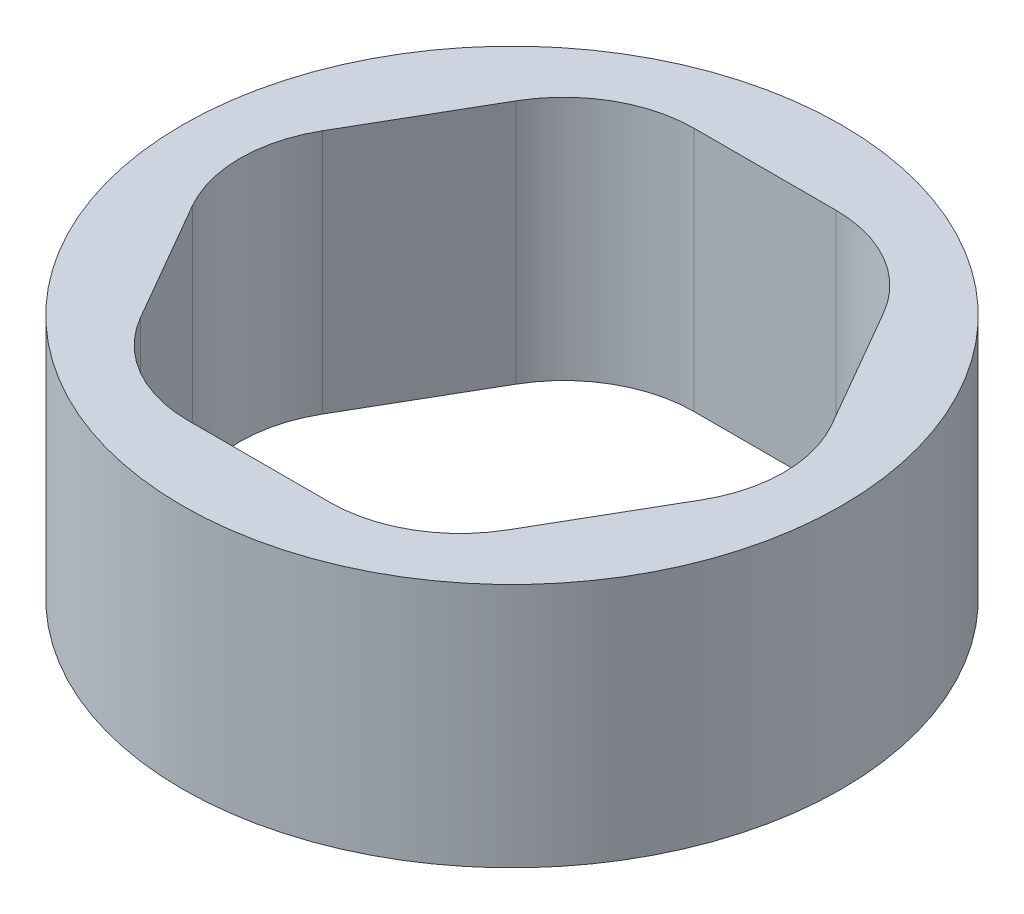
SolidWorks part; units mm, degrees
ref_plane "前视基准面" through (0, 0, 0) normal (0, 0, 1) x (1, 0, 0)
ref_plane "上视基准面" through (0, 0, 0) normal (0, 1, 0) x (1, 0, 0)
ref_plane "右视基准面" through (0, 0, 0) normal (1, 0, 0) x (0, 0, -1)
sketch "草图1" plane through (0, 0, 0) normal (0, 1, 0) x (1, 0, 0)
  line L1 (9.5263, -16.5) -> (19.0526, 0)
  line L2 (19.0526, 0) -> (9.5263, 16.5)
  line L3 (9.5263, 16.5) -> (-9.5263, 16.5)
  line L4 (-9.5263, 16.5) -> (-19.0526, 0)
  line L5 (-19.0526, 0) -> (-9.5263, -16.5)
  line L6 (-9.5263, -16.5) -> (9.5263, -16.5)
  circle A0 centre (0, 0) radius 16.5 construction
  circle A1 centre (0, 0) radius 21.5
  dimension "D1" = 33
  dimension "D2" = 5
extrude "凸台-拉伸1" add sketch "草图1" along normal blind 16
fillet "圆角1" radius 8.5 6 edges at (-9.5263, 8, 16.5) (9.5263, 8, 16.5) (19.0526, 8, 0) (9.5263, 8, -16.5) (-9.5263, 8, -16.5) (-19.0526, 8, 0)
